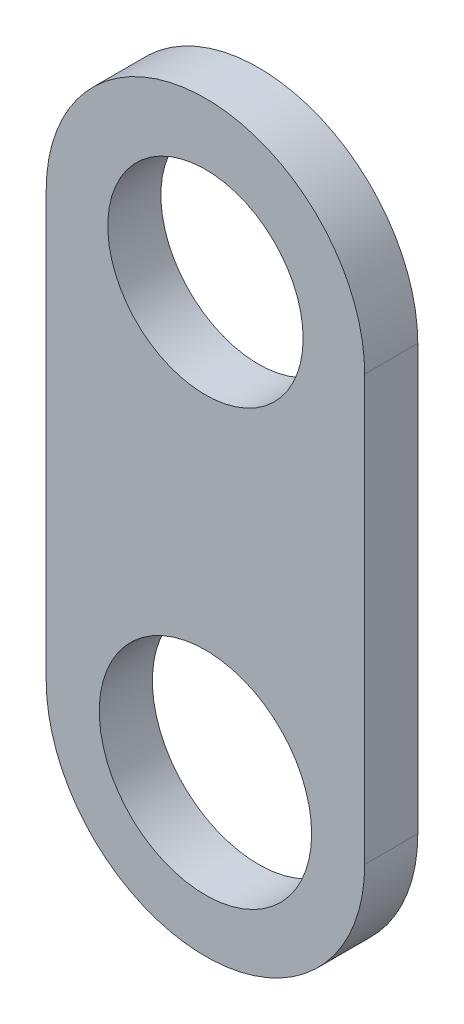
SolidWorks part; units mm, degrees
material "ASTM A36 Steel"
ref_plane "Front Plane" through (0, 0, 0) normal (0, 0, 1) x (1, 0, 0)
ref_plane "Top Plane" through (0, 0, 0) normal (0, 1, 0) x (1, 0, 0)
ref_plane "Right Plane" through (0, 0, 0) normal (1, 0, 0) x (0, 0, -1)
sketch "Sketch1" plane through (0, 0, 0) normal (0, 0, 1) x (1, 0, 0)
  line L0 (0, 34.1877) -> (0, -16.6123)
  line L1 (0, -16.6123) -> (38.1, -16.6123)
  line L2 (38.1, -16.6123) -> (38.1, 34.1877)
  line L3 (38.1, 34.1877) -> (0, 34.1877)
  arc A0 (0, -16.6123) -> (38.1, -16.6123) centre (19.05, -16.6123) ccw
  arc A1 (38.1, 34.1877) -> (0, 34.1877) centre (19.05, 34.1877) ccw
  circle A2 centre (19.05, 34.1877) radius 11.684
  circle A3 centre (19.05, -16.6123) radius 12.7
  dimension "D1" = 23.368
  dimension "D4" = 25.4
  dimension "D2" = 38.1
  dimension "D3" = 50.8
extrude "Boss-Extrude1" add sketch "Sketch1" along normal blind 6.35 contours A2 L3 A1 | A3 L1 A0 | A3 L1 L2 L3 A2 L0
equation "\"Lower D\"= 1.00in"
equation "\"Yield Stress\"= 36000"
equation "\"E\"= 29000000"
equation "\"Length\"= 2in"
equation "\"t\" = 0.250in"
equation "\"SF\"= 4"
equation "\"Stress A\"= \"Yield Stress\" / \"SF\""
equation "\"F\"= 600"
equation "\"Stress Area\"= \"F\" / \"Stress A\""
equation "\"Stress Width\" = \"Stress Area\" / \"t\" + \"Lower D\""
equation "\"Deflection\"= 0.005in"
equation "\"Deflect Area\"= 0.004in"
equation "\"Deflect Width\"= 0.016in"
equation "\"D1@Sketch1\"=0.92in"
equation "\"D2@Sketch1\"=1.50"
equation "\"D4@Sketch1\"=\"Lower D\""
equation "\"D3@Sketch1\"=\"Length\""
